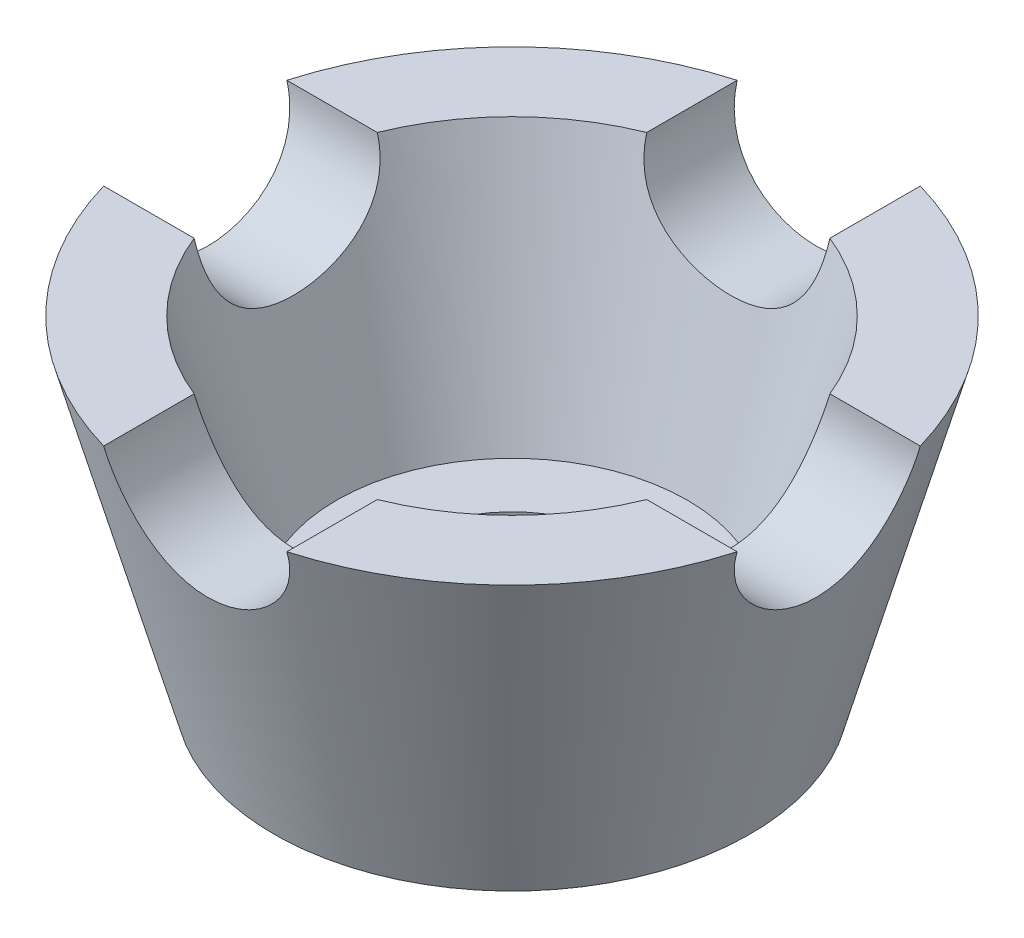
SolidWorks part; units mm, degrees
ref_plane "Front Plane" through (0, 0, 0) normal (0, 0, 1) x (1, 0, 0)
ref_plane "Top Plane" through (0, 0, 0) normal (0, 1, 0) x (1, 0, 0)
ref_plane "Right Plane" through (0, 0, 0) normal (1, 0, 0) x (0, 0, -1)
sketch "Sketch1" plane through (0, 0, 0) normal (0, 0, 1) x (1, 0, 0)
  line L0 (0, 0) -> (0, 36) construction
  line L1 (6, 36) -> (36, 36)
  line L2 (36, 36) -> (26, 0)
  line L3 (26, 0) -> (0, 0)
  line L4 (26.6592, 36) -> (19.1592, 9)
  line L5 (19.1592, 9) -> (0, 9)
  arc A0 (6, 36) -> (0, 30) centre (0, 36) cw
  point P10 (0, 36.354)
  point P11 (0, 0)
  point P12 (29.3194, 36)
  dimension "D4" = 6
  dimension "D1" = 9
  dimension "D2" = 36
  dimension "D3" = 26
  dimension "D5" = 36
  dimension "D6" = 9
revolve "Revolve1" add sketch "Sketch1" angle 360 about L0
sketch "Sketch2" plane through (0, 0, 0) normal (1, 0, 0) x (0, 0, -1)
  line L0 (0, 36) -> (0, 0) construction
  line L1 (26.6592, 36) -> (-26.6592, 36) construction
  line L2 (36, 36) -> (-36, 36) construction
  line L3 (-10, 36) -> (10, 36)
  arc A0 (-10, 36) -> (10, 36) centre (0, 36) ccw
  dimension "D1" = 10
extrude "Cut-Extrude1" cut sketch "Sketch2" against normal through all both and the other way through all
pattern_circular "CirPattern1" count 4 over 360 of "Cut-Extrude1"
sketch "Sketch4" plane through (0, 0, 0) normal (0, -1, 0) x (1, 0, 0)
  circle A0 centre (0, 0) radius 12
  dimension "D1" = 24
extrude "Cut-Extrude2" cut sketch "Sketch4" against normal through all both
